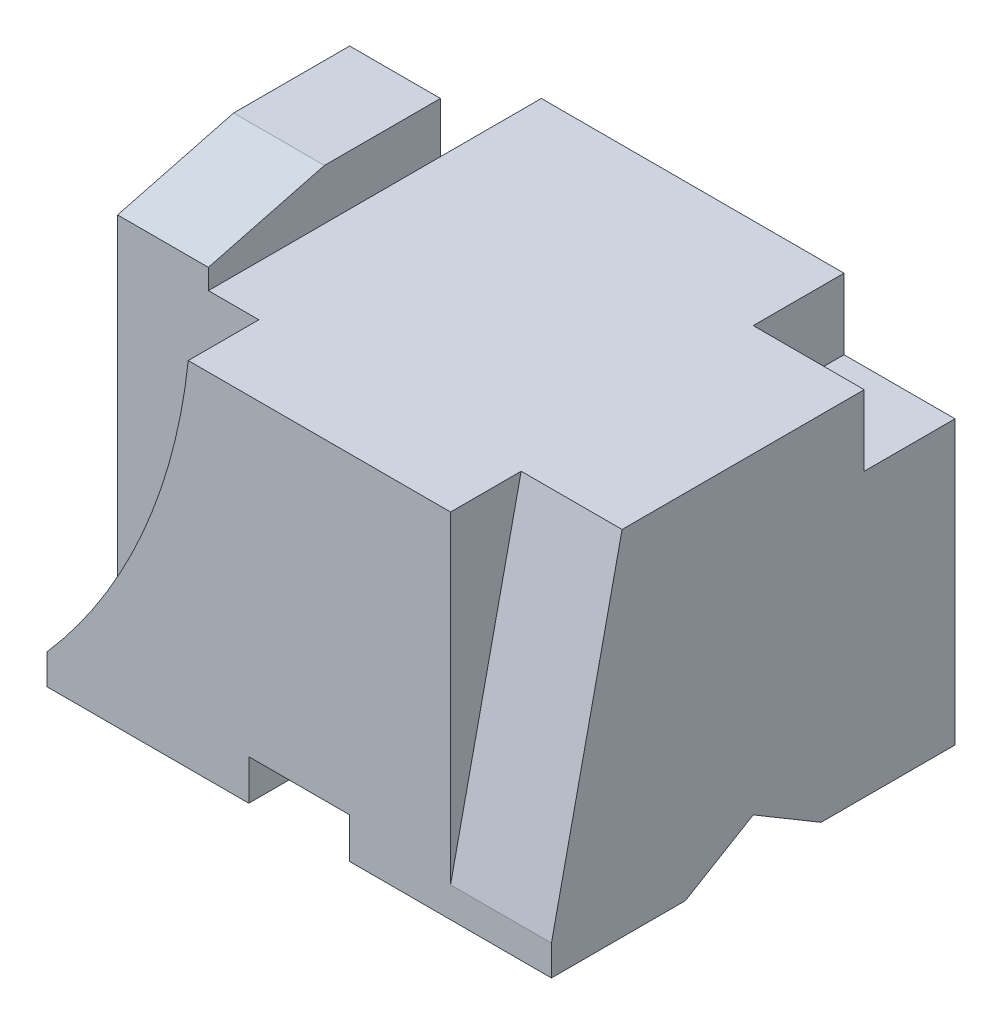
SolidWorks part; units mm, degrees
ref_plane "Спереди" through (0, 0, 0) normal (0, 0, 1) x (1, 0, 0)
ref_plane "Сверху" through (0, 0, 0) normal (0, 1, 0) x (1, 0, 0)
ref_plane "Справа" through (0, 0, 0) normal (1, 0, 0) x (0, 0, -1)
sketch "Эскиз1" plane through (0, 0, 0) normal (0, 1, 0) x (1, 0, 0)
  line L1 (0, 0) -> (50, 0)
  line L2 (0, 0) -> (0, 40)
  line L3 (0, 40) -> (50, 40)
  line L4 (50, 0) -> (50, 40)
  dimension "D1" = 50
  dimension "D2" = 40
extrude "Бобышка-Вытянуть1" add sketch "Эскиз1" along normal blind 40
sketch "Эскиз4" plane through (0, 0, 0) normal (0, 0, 1) x (1, 0, 0)
  line L0 (25, 40) -> (25, 0) construction
  line L1 (0, 40) -> (50, 40) construction
  line L2 (0, 0) -> (50, 0) construction
  line L3 (20, 4) -> (20, 0)
  line L4 (20, 4) -> (30, 4)
  line L5 (30, 4) -> (30, 0)
  line M7 (0, 0) -> (50, 0)
  dimension "D1" = 5
  dimension "D2" = 4
extrude "Вырез-Вытянуть1" cut sketch "Эскиз4" against normal through all and the other way through all contours L0 L4 L3 M7 | L4 L0 L5 M7
sketch "Эскиз5" plane through (0, 0, 0) normal (-1, 0, 0) x (0, 0, 1)
  line L0 (-20, 40) -> (-20, 0) construction
  line L1 (-40, 40) -> (0, 40) construction
  line L2 (-40, 0) -> (0, 0) construction
  line L3 (-26.7216, 0) -> (-20, 4)
  line L4 (-40, 40) -> (-40, 0) construction
  line L5 (-13.2784, 0) -> (-20, 4)
  dimension "D1" = 4
  dimension "D2" = 13.2784
extrude "Вырез-Вытянуть3" cut sketch "Эскиз5" against normal through all and the other way through all contours L0 L3 L1 | L5 L0 L1
sketch "Эскиз6" plane through (0, 0, 0) normal (0, 0, 1) x (1, 0, 0)
  line L0 (9, 40) -> (9, 35)
  line L1 (0, 40) -> (50, 40) construction
  line L2 (9, 35) -> (50, 35)
  line L3 (50, 40) -> (50, 0) construction
  line M8 (50, 0) -> (50, 40)
  line M9 (50, 40) -> (0, 40)
  dimension "D1" = 5
  dimension "D2" = 41
extrude "Вырез-Вытянуть4" cut sketch "Эскиз6" against normal through all and the other way through all contours L0 L2 M8 M9
sketch "Эскиз8" plane through (0, 0, 0) normal (0, 0, 1) x (1, 0, 0)
  line L0 (50, 35) -> (9, 35) construction
  line L1 (0, 40) -> (0, 0) construction
  line L2 (0, 0) -> (20, 0) construction
  line L3 (9, 35) -> (9, 40) construction
  arc A0 (14, 35) -> (0, 3) centre (-43.671, 41.1686) cw
  line M2 (50, 35) -> (9, 35)
  line M3 (9, 35) -> (9, 40)
  line M4 (9, 40) -> (0, 40)
  line M5 (0, 40) -> (0, 0)
  dimension "D1" = 58
  dimension "D2" = 3
  dimension "D3" = 5
extrude "Вырез-Вытянуть5" cut sketch "Эскиз8" against normal blind 7 and the other way through all contours A0 M2 M3 M4 M5
sketch "Эскиз9" plane through (50, 0, 0) normal (1, 0, 0) x (0, 0, -1)
  line L0 (0, 3) -> (7, 35)
  line L1 (0, 35) -> (0, 0) construction
  line L2 (0, 0) -> (13.2784, 0) construction
  line M3 (40, 35) -> (0, 35)
  line M4 (0, 35) -> (0, 0)
  dimension "D1" = 3
extrude "Вырез-Вытянуть6" cut sketch "Эскиз9" against normal blind 10 and the other way through all contours L0 M4 M3
sketch "Эскиз11" plane through (0, 0, 0) normal (-1, 0, 0) x (0, 0, 1)
  line L0 (-40, 22) -> (-30, 22)
  line L1 (-40, 40) -> (-40, 0) construction
  line L2 (-30, 22) -> (-30, 40)
  line L3 (-40, 40) -> (-7, 40) construction
  dimension "D1" = 18
  dimension "D2" = 10
extrude "Вырез-Вытянуть7" cut sketch "Эскиз11" against normal blind 9 and the other way through all
sketch "Эскиз14" plane through (0, 0, 0) normal (-1, 0, 0) x (0, 0, 1)
  line L0 (-18.5, 40) -> (-7, 37)
  line L1 (-30, 40) -> (-7, 40) construction
  line L2 (-7, 40) -> (-7, 3) construction
  line M11 (-7, 3) -> (-7, 40)
  line M12 (-7, 40) -> (-30, 40)
  dimension "D1" = 3
extrude "Вырез-Вытянуть8" cut sketch "Эскиз14" against normal blind 9 and the other way through all contours L0 M12 M11
sketch "Эскиз15" plane through (0, 0, -40) normal (0, 0, -1) x (-1, 0, 0)
  line L0 (-50, 28) -> (-39, 28)
  line L1 (-50, 35) -> (-50, 0) construction
  line L2 (-39, 28) -> (-39, 35)
  line L3 (-9, 35) -> (-50, 35) construction
  line M5 (-9, 35) -> (-50, 35)
  line M6 (-50, 35) -> (-50, 0)
  dimension "D1" = 7
  dimension "D2" = 11
extrude "Вырез-Вытянуть9" cut sketch "Эскиз15" against normal blind 9 and the other way through all contours L0 L2 M5 M6
